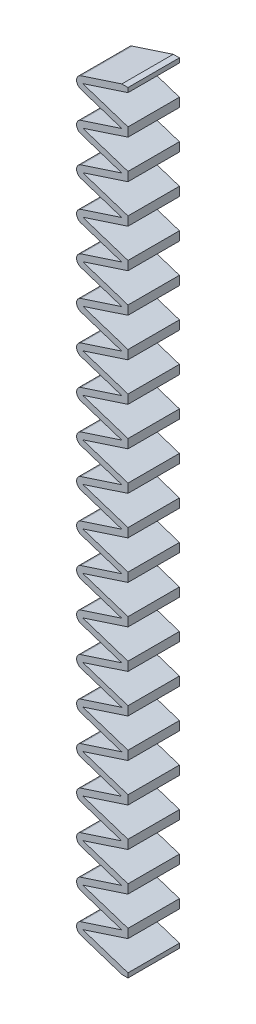
SolidWorks part; units mm, degrees
ref_plane "Front Plane" through (0, 0, 0) normal (0, 0, 1) x (1, 0, 0)
ref_plane "Top Plane" through (0, 0, 0) normal (0, 1, 0) x (1, 0, 0)
ref_plane "Right Plane" through (0, 0, 0) normal (1, 0, 0) x (0, 0, -1)
sketch "Sketch1" plane through (0, 0, 0) normal (0, 0, 1) x (1, 0, 0)
  line L0 (-5, 72.1199) -> (-4.8121, 72.1814) construction
  line L1 (-5, -75) -> (5, -75) construction
  line L2 (-5, -75) -> (-5, 75) construction
  line L3 (-5, 75) -> (5, 75) construction
  line L4 (5, -75) -> (5, 75) construction
  line L5 (-5, -75) -> (5, 75) construction
  line L6 (-5, 75) -> (5, -75) construction
  line L7 (-5, 72.1199) -> (-5, 70.3801) construction
  line L8 (-5, 70.3801) -> (-4.6851, 70.2771) construction
  line L9 (5, 74.1301) -> (5, 75)
  line L10 (-4.1733, 62.6095) -> (3.8, 60)
  line L11 (5, 74.1301) -> (-3.8, 71.25)
  line L12 (-3.8, 71.25) -> (5, 68.3699)
  line L13 (-3.8, 71.25) -> (-5, 71.25) construction
  line L15 (5, 68.3699) -> (5, 67.5)
  line L16 (-4.1733, 72.3905) -> (3.8, 75)
  line L17 (-4.1733, 70.1095) -> (3.8, 67.5)
  line L18 (-4.1733, 64.8905) -> (3.8, 67.5)
  line L19 (-3.8, 63.75) -> (5, 60.8699)
  line L20 (5, 66.6301) -> (-3.8, 63.75)
  line L21 (5, 60.8699) -> (5, 60)
  line L22 (5, 66.6301) -> (5, 67.5)
  line L23 (-4.1733, 55.1095) -> (3.8, 52.5)
  line L24 (-4.1733, 57.3905) -> (3.8, 60)
  line L25 (-3.8, 56.25) -> (5, 53.3699)
  line L26 (5, 59.1301) -> (-3.8, 56.25)
  line L27 (5, 53.3699) -> (5, 52.5)
  line L28 (5, 59.1301) -> (5, 60)
  line L29 (-4.1733, 47.6095) -> (3.8, 45)
  line L30 (-4.1733, 49.8905) -> (3.8, 52.5)
  line L31 (-3.8, 48.75) -> (5, 45.8699)
  line L32 (5, 51.6301) -> (-3.8, 48.75)
  line L33 (5, 45.8699) -> (5, 45)
  line L34 (5, 51.6301) -> (5, 52.5)
  line L35 (-4.1733, 40.1095) -> (3.8, 37.5)
  line L36 (-4.1733, 42.3905) -> (3.8, 45)
  line L37 (-3.8, 41.25) -> (5, 38.3699)
  line L38 (5, 44.1301) -> (-3.8, 41.25)
  line L39 (5, 38.3699) -> (5, 37.5)
  line L40 (5, 44.1301) -> (5, 45)
  line L41 (-4.1733, 32.6095) -> (3.8, 30)
  line L42 (-4.1733, 34.8905) -> (3.8, 37.5)
  line L43 (-3.8, 33.75) -> (5, 30.8699)
  line L44 (5, 36.6301) -> (-3.8, 33.75)
  line L45 (5, 30.8699) -> (5, 30)
  line L46 (5, 36.6301) -> (5, 37.5)
  line L47 (-4.1733, 25.1095) -> (3.8, 22.5)
  line L48 (-4.1733, 27.3905) -> (3.8, 30)
  line L49 (-3.8, 26.25) -> (5, 23.3699)
  line L50 (5, 29.1301) -> (-3.8, 26.25)
  line L51 (5, 23.3699) -> (5, 22.5)
  line L52 (5, 29.1301) -> (5, 30)
  line L53 (-4.1733, 17.6095) -> (3.8, 15)
  line L54 (-4.1733, 19.8905) -> (3.8, 22.5)
  line L55 (-3.8, 18.75) -> (5, 15.8699)
  line L56 (5, 21.6301) -> (-3.8, 18.75)
  line L57 (5, 15.8699) -> (5, 15)
  line L58 (5, 21.6301) -> (5, 22.5)
  line L59 (-4.1733, 10.1095) -> (3.8, 7.5)
  line L60 (-4.1733, 12.3905) -> (3.8, 15)
  line L61 (-3.8, 11.25) -> (5, 8.3699)
  line L62 (5, 14.1301) -> (-3.8, 11.25)
  line L63 (5, 8.3699) -> (5, 7.5)
  line L64 (5, 14.1301) -> (5, 15)
  line L65 (-4.1733, 2.6095) -> (3.8, 0)
  line L66 (-4.1733, 4.8905) -> (3.8, 7.5)
  line L67 (-3.8, 3.75) -> (5, 0.8699)
  line L68 (5, 6.6301) -> (-3.8, 3.75)
  line L69 (5, 0.8699) -> (5, 0)
  line L70 (5, 6.6301) -> (5, 7.5)
  line L71 (-4.1733, -4.8905) -> (3.8, -7.5)
  line L72 (-4.1733, -2.6095) -> (3.8, 0)
  line L73 (-3.8, -3.75) -> (5, -6.6301)
  line L74 (5, -0.8699) -> (-3.8, -3.75)
  line L75 (5, -6.6301) -> (5, -7.5)
  line L76 (5, -0.8699) -> (5, 0)
  line L77 (-4.1733, -12.3905) -> (3.8, -15)
  line L78 (-4.1733, -10.1095) -> (3.8, -7.5)
  line L79 (-3.8, -11.25) -> (5, -14.1301)
  line L80 (5, -8.3699) -> (-3.8, -11.25)
  line L81 (5, -14.1301) -> (5, -15)
  line L82 (5, -8.3699) -> (5, -7.5)
  line L83 (-4.1733, -19.8905) -> (3.8, -22.5)
  line L84 (-4.1733, -17.6095) -> (3.8, -15)
  line L85 (-3.8, -18.75) -> (5, -21.6301)
  line L86 (5, -15.8699) -> (-3.8, -18.75)
  line L87 (5, -21.6301) -> (5, -22.5)
  line L88 (5, -15.8699) -> (5, -15)
  line L89 (-4.1733, -27.3905) -> (3.8, -30)
  line L90 (-4.1733, -25.1095) -> (3.8, -22.5)
  line L91 (-3.8, -26.25) -> (5, -29.1301)
  line L92 (5, -23.3699) -> (-3.8, -26.25)
  line L93 (5, -29.1301) -> (5, -30)
  line L94 (5, -23.3699) -> (5, -22.5)
  line L95 (-4.1733, -34.8905) -> (3.8, -37.5)
  line L96 (-4.1733, -32.6095) -> (3.8, -30)
  line L97 (-3.8, -33.75) -> (5, -36.6301)
  line L98 (5, -30.8699) -> (-3.8, -33.75)
  line L99 (5, -36.6301) -> (5, -37.5)
  line L100 (5, -30.8699) -> (5, -30)
  line L101 (-4.1733, -42.3905) -> (3.8, -45)
  line L102 (-4.1733, -40.1095) -> (3.8, -37.5)
  line L103 (-3.8, -41.25) -> (5, -44.1301)
  line L104 (5, -38.3699) -> (-3.8, -41.25)
  line L105 (5, -44.1301) -> (5, -45)
  line L106 (5, -38.3699) -> (5, -37.5)
  line L107 (-4.1733, -49.8905) -> (3.8, -52.5)
  line L108 (-4.1733, -47.6095) -> (3.8, -45)
  line L109 (-3.8, -48.75) -> (5, -51.6301)
  line L110 (5, -45.8699) -> (-3.8, -48.75)
  line L111 (5, -51.6301) -> (5, -52.5)
  line L112 (5, -45.8699) -> (5, -45)
  line L113 (-4.1733, -57.3905) -> (3.8, -60)
  line L114 (-4.1733, -55.1095) -> (3.8, -52.5)
  line L115 (-3.8, -56.25) -> (5, -59.1301)
  line L116 (5, -53.3699) -> (-3.8, -56.25)
  line L117 (5, -59.1301) -> (5, -60)
  line L118 (5, -53.3699) -> (5, -52.5)
  line L119 (-4.1733, -64.8905) -> (3.8, -67.5)
  line L120 (-4.1733, -62.6095) -> (3.8, -60)
  line L121 (-3.8, -63.75) -> (5, -66.6301)
  line L122 (5, -60.8699) -> (-3.8, -63.75)
  line L123 (5, -66.6301) -> (5, -67.5)
  line L124 (5, -60.8699) -> (5, -60)
  line L125 (-4.1733, -72.3905) -> (3.8, -75)
  line L126 (-4.1733, -70.1095) -> (3.8, -67.5)
  line L127 (-3.8, -71.25) -> (5, -74.1301)
  line L128 (5, -68.3699) -> (-3.8, -71.25)
  line L129 (5, -74.1301) -> (5, -75)
  line L130 (5, -68.3699) -> (5, -67.5)
  line L131 (5, 75) -> (3.8, 75)
  line L132 (5, -75) -> (3.8, -75)
  arc A0 (-4.1733, 72.3905) -> (-4.1733, 70.1095) centre (-3.8, 71.25) ccw
  arc A1 (-4.1733, 64.8905) -> (-4.1733, 62.6095) centre (-3.8, 63.75) ccw
  arc A2 (-4.1733, 57.3905) -> (-4.1733, 55.1095) centre (-3.8, 56.25) ccw
  arc A3 (-4.1733, 49.8905) -> (-4.1733, 47.6095) centre (-3.8, 48.75) ccw
  arc A4 (-4.1733, 42.3905) -> (-4.1733, 40.1095) centre (-3.8, 41.25) ccw
  arc A5 (-4.1733, 34.8905) -> (-4.1733, 32.6095) centre (-3.8, 33.75) ccw
  arc A6 (-4.1733, 27.3905) -> (-4.1733, 25.1095) centre (-3.8, 26.25) ccw
  arc A7 (-4.1733, 19.8905) -> (-4.1733, 17.6095) centre (-3.8, 18.75) ccw
  arc A8 (-4.1733, 12.3905) -> (-4.1733, 10.1095) centre (-3.8, 11.25) ccw
  arc A9 (-4.1733, 4.8905) -> (-4.1733, 2.6095) centre (-3.8, 3.75) ccw
  arc A10 (-4.1733, -2.6095) -> (-4.1733, -4.8905) centre (-3.8, -3.75) ccw
  arc A11 (-4.1733, -10.1095) -> (-4.1733, -12.3905) centre (-3.8, -11.25) ccw
  arc A12 (-4.1733, -17.6095) -> (-4.1733, -19.8905) centre (-3.8, -18.75) ccw
  arc A13 (-4.1733, -25.1095) -> (-4.1733, -27.3905) centre (-3.8, -26.25) ccw
  arc A14 (-4.1733, -32.6095) -> (-4.1733, -34.8905) centre (-3.8, -33.75) ccw
  arc A15 (-4.1733, -40.1095) -> (-4.1733, -42.3905) centre (-3.8, -41.25) ccw
  arc A16 (-4.1733, -47.6095) -> (-4.1733, -49.8905) centre (-3.8, -48.75) ccw
  arc A17 (-4.1733, -55.1095) -> (-4.1733, -57.3905) centre (-3.8, -56.25) ccw
  arc A18 (-4.1733, -62.6095) -> (-4.1733, -64.8905) centre (-3.8, -63.75) ccw
  arc A19 (-4.1733, -70.1095) -> (-4.1733, -72.3905) centre (-3.8, -71.25) ccw
  point P0 (0, 0)
  point P14 (-5, 71.25)
  dimension "D1" = 10
  dimension "D2" = 150
  dimension "D3" = 1.2
  dimension "D4" = 1.2
  dimension "D6" = 20
extrude "Boss-Extrude1" add sketch "Sketch1" along normal blind 10
